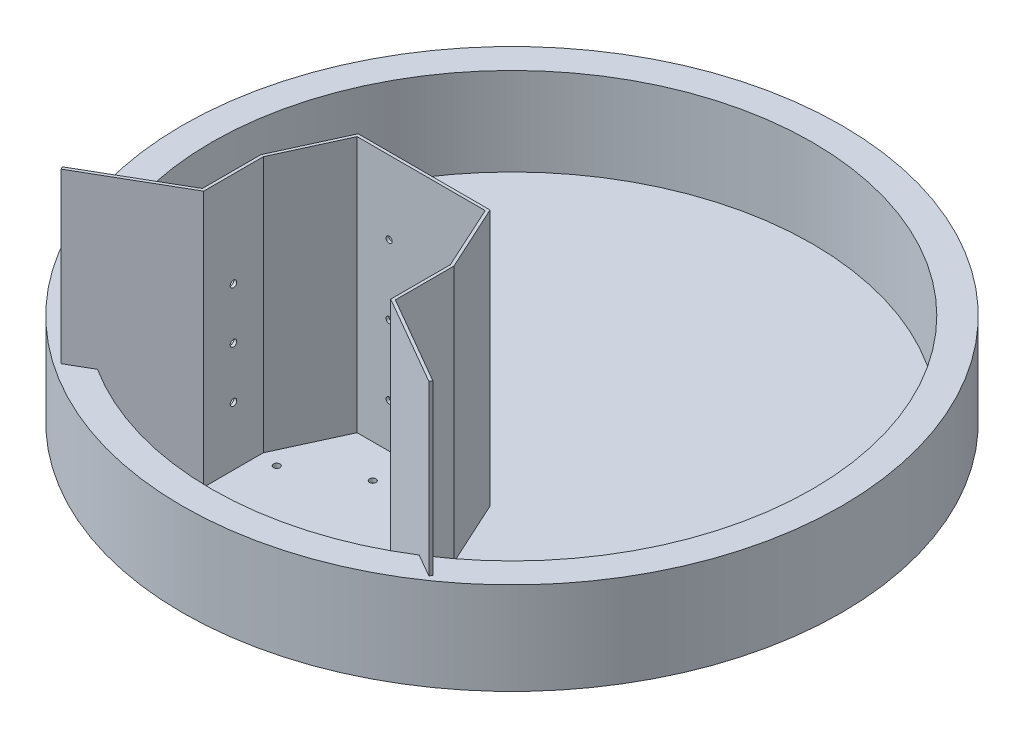
SolidWorks part; units mm, degrees
ref_plane "Front Plane" through (0, 0, 0) normal (0, 0, 1) x (1, 0, 0)
ref_plane "Top Plane" through (0, 0, 0) normal (0, 1, 0) x (1, 0, 0)
ref_plane "Right Plane" through (0, 0, 0) normal (1, 0, 0) x (0, 0, -1)
sketch "Sketch1" plane through (0, 0, 0) normal (0, 1, 0) x (1, 0, 0)
  line L0 (0, 0) -> (-45, 0)
  line L1 (-45, 0) -> (-65.8333, -45.453)
  line L2 (-65.8333, -45.453) -> (-65.8333, -85.453)
  line L3 (-65.8333, -85.453) -> (-126.4551, -120.453)
  dimension "D1" = 45
  dimension "D2" = 50
  dimension "D3" = 40
  dimension "D4" = 70
  dimension "D5" = 120
  dimension "D7" = 80
extrude "Extrude-Thin1" add sketch "Sketch1" along normal blind 175 thin contours L0 L1 L2 L3 thin type one direction reverse wall 2
sketch "Sketch2" plane through (0, 0, 2) normal (0, 0, 1) x (1, 0, 0)
  line L0 (-21.8583, 175) -> (-21.8583, 0) construction
  line L1 (0, 175) -> (-43.7166, 175) construction
  line L2 (0, 0) -> (-43.7166, 0) construction
  circle A0 centre (-21.8583, 30) radius 2.1
  circle A1 centre (-21.8583, 77.5) radius 2.1
  circle A2 centre (-21.8583, 125) radius 2.1
  dimension "D4" = 4.2
  dimension "D5" = 4.2
  dimension "D6" = 4.2
  dimension "D1" = 30
  dimension "D2" = 47.5
  dimension "D3" = 47.5
extrude "Cut-Extrude1" cut sketch "Sketch2" against normal up to next
sketch "Sketch3" plane through (-63.8333, 0, 0) normal (1, 0, 0) x (0, 0, -1)
  line L0 (-66.2486, 175) -> (-66.2486, 0) construction
  line L1 (-45.8895, 175) -> (-86.6077, 175) construction
  line L2 (-45.8895, 0) -> (-86.6077, 0) construction
  circle A0 centre (-66.2486, 40) radius 2.25
  circle A1 centre (-66.2486, 75) radius 2.25
  circle A2 centre (-66.2486, 110) radius 2.25
  dimension "D4" = 4.5
  dimension "D5" = 4.5
  dimension "D6" = 4.5
  dimension "D1" = 40
  dimension "D2" = 75
  dimension "D3" = 110
extrude "Cut-Extrude2" cut sketch "Sketch3" against normal up to next
mirror "Mirror1" about plane through (0, 0, 0) normal (1, 0, 0) of "Cut-Extrude2", "Cut-Extrude1", "Extrude-Thin1"
sketch "Sketch4" plane through (0, 0, 0) normal (0, -1, 0) x (1, 0, 0)
  line L0 (0, -60) -> (-194.8557, 52.5) construction
  line L1 (0, -60) -> (194.8557, 52.5) construction
  line L2 (0, -60) -> (0, -285) construction
  line L3 (-63.8333, 86.6077) -> (-125.4551, 122.185) construction
  circle A0 centre (0, -60) radius 225 construction
  circle A1 centre (0, -60) radius 225
  point P4 (139.7492, 116.3382)
  point P7 (171.6169, 85.5082)
  dimension "D1" = 120
  dimension "D2" = 120
extrude "Boss-Extrude1" add sketch "Sketch4" along normal blind 3
sketch "Sketch5" plane through (0, 0, 0) normal (0, 1, 0) x (1, 0, 0)
  line L0 (-79.7034, -127.0198) -> (71.6342, -39.6449) construction
  line L1 (-63.8333, -86.6077) -> (-125.4551, -122.185) construction
  line L2 (-4.0346, -83.3324) -> (33.3437, -148.0735) construction
  line L3 (43.7166, -2) -> (-43.7166, -2) construction
  line L4 (43.5, -117.6647) -> (-10, -25) construction
  circle A0 centre (-10, -25) radius 2.2
  circle A1 centre (43.5, -117.6647) radius 2.2
  circle A2 centre (1.9308, -141.6647) radius 2.2
  circle A3 centre (-51.5692, -49) radius 2.2
  point P12 (-10, -25)
  dimension "D5" = 4.4
  dimension "D6" = 4.4
  dimension "D7" = 4.4
  dimension "D8" = 4.4
  dimension "D1" = 48
  dimension "D2" = 107
  dimension "D3" = 48
  dimension "D4" = 107
  dimension "D9" = 53.5
  dimension "D11" = 24
  dimension "D12" = 24
  dimension "D13" = 23
  dimension "D14" = 10
extrude "Cut-Extrude3" cut sketch "Sketch5" against normal blind 3
sketch "Sketch6" plane through (0, 0, 0) normal (0, 1, 0) x (1, 0, 0)
  circle A0 centre (0, 60) radius 225 construction
  circle A1 centre (0, 60) radius 225
  circle A2 centre (0, 60) radius 205
  dimension "D1" = 20
extrude "Boss-Extrude2" add sketch "Sketch6" along normal blind 60
